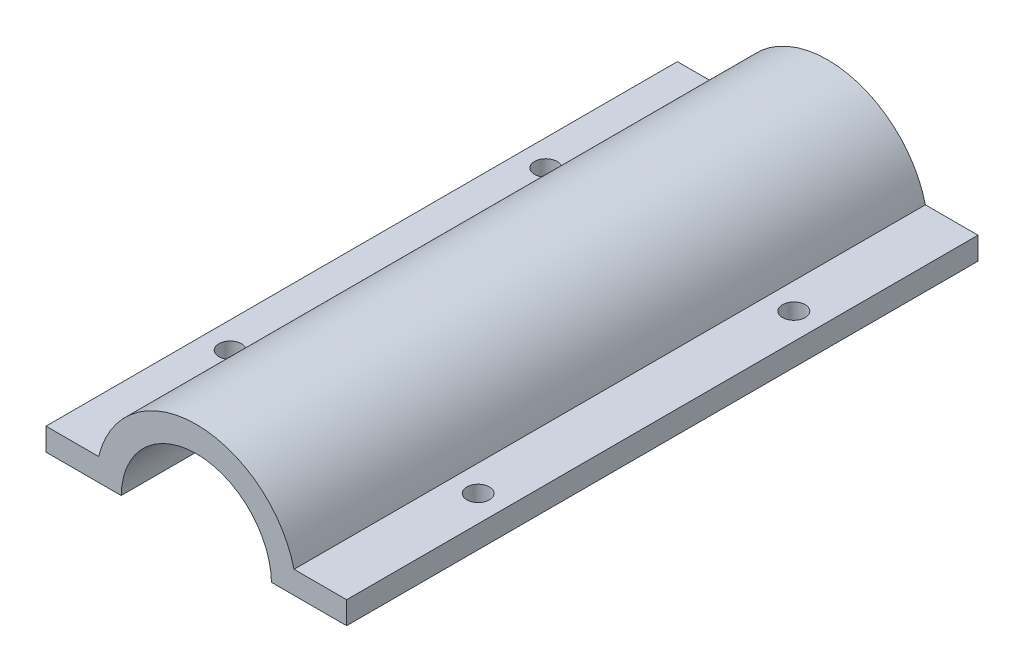
SolidWorks part; units mm, degrees
ref_plane "Спереди" through (0, 0, 0) normal (0, 0, 1) x (1, 0, 0)
ref_plane "Сверху" through (0, 0, 0) normal (0, 1, 0) x (1, 0, 0)
ref_plane "Справа" through (0, 0, 0) normal (1, 0, 0) x (0, 0, -1)
sketch "Эскиз1" plane through (0, 0, 0) normal (0, 0, 1) x (1, 0, 0)
  line L0 (0, 0) -> (0, 10) construction
  line L1 (0, 0) -> (-10, 0) construction
  line L2 (0, 0) -> (10, 0) construction
  line L3 (0, 0) -> (9.9985, 0.1745) construction
  line L4 (0, 0) -> (-9.9985, 0.1745) construction
  line L7 (-9.9985, 0.1745) -> (-19.9985, 0.1745)
  line L8 (-19.9985, 0.1745) -> (-19.9985, 3.1745)
  line L9 (-19.9985, 3.1745) -> (-12.9985, 3.1745)
  line L10 (9.9985, 0.1745) -> (19.9985, 0.1745)
  line L11 (19.9985, 0.1745) -> (19.9985, 3.1745)
  line L12 (19.9985, 3.1745) -> (12.9985, 3.1745)
  arc A0 (0, 10) -> (9.9985, 0.1745) centre (0, 0) cw
  arc A1 (0, 10) -> (-9.9985, 0.1745) centre (0, 0) ccw
  arc A2 (-12.9985, 3.1745) -> (12.9985, 3.1745) centre (0, 0) cw
  point P9 (10.0883, 0.1745)
  point P16 (-10.1981, 0.1745)
  dimension "D1" = 10
  dimension "D5" = 13.3805
  dimension "D2" = 3
  dimension "D3" = 10
  dimension "D4" = 7
extrude "Бобышка-Вытянуть1" add sketch "Эскиз1" along normal blind 84
sketch "Эскиз2" plane through (0, 3.1745, 0) normal (0, 1, 0) x (1, 0, 0)
  line L0 (-16.4985, 0) -> (-16.4985, -84) construction
  line L1 (-12.9985, 0) -> (-19.9985, 0) construction
  line L2 (-12.9985, -84) -> (-19.9985, -84) construction
  line L3 (-19.9985, -42) -> (19.9985, -42) construction
  line L4 (-19.9985, -84) -> (-19.9985, 0) construction
  line L5 (19.9985, -84) -> (19.9985, 0) construction
  line L6 (16.4985, 0) -> (16.4985, -84) construction
  line L7 (19.9985, 0) -> (12.9985, 0) construction
  line L8 (19.9985, -84) -> (12.9985, -84) construction
  circle A0 centre (-16.4985, -21) radius 1.5
  circle A1 centre (-16.4985, -63) radius 1.5
  circle A2 centre (16.4985, -21) radius 1.5
  circle A3 centre (16.4985, -63) radius 1.5
  point P16 (-16.4985, -42)
  point P27 (0, 0)
  dimension "D1" = 21
  dimension "D3" = 3
  dimension "D4" = 32.997
  dimension "D5" = 42
  dimension "D2" = 21
extrude "Вырез-Вытянуть1" cut sketch "Эскиз2" against normal through all
